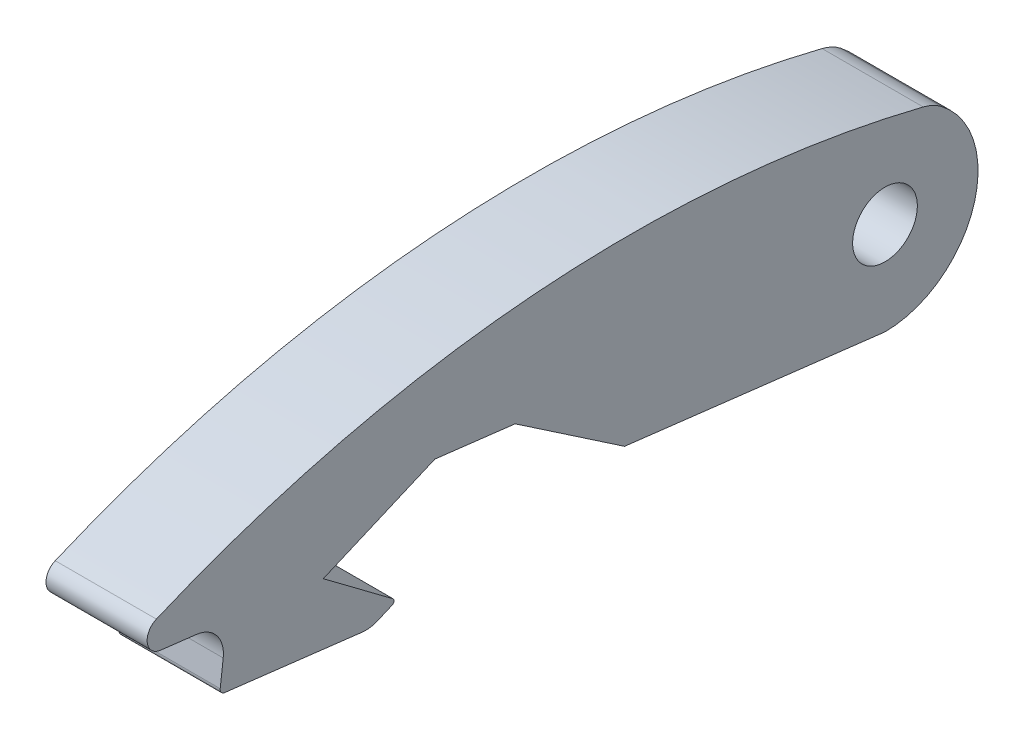
SolidWorks part; units mm, degrees
ref_plane "Front Plane" through (0, 0, 0) normal (1, 0, 0) x (0, 1, 0)
ref_plane "Top Plane" through (0, 0, 0) normal (0, 0, 1) x (0, 1, 0)
ref_plane "Right Plane" through (0, 0, 0) normal (0, 1, 0) x (-1, 0, 0)
sketch "Sketch2" plane through (0, 0, 0) normal (1, 0, 0) x (0, 1, 0)
  line L0 (0, 38.5) -> (-0.7118, 32.5424)
  line L1 (0, 0) -> (0, -1.2336) construction
  line L2 (3.9837, -2.3) -> (0, 0) construction
  line L3 (-0.7118, 32.5424) -> (-3.6906, 32.8983)
  line L6 (-4.877, 22.9689) -> (-1.2817, 27.7725)
  line L8 (-3.0613, 12.8784) -> (-4.6, 0)
  line L9 (-3.6906, 32.8983) -> (-4.877, 22.9689)
  line L10 (-1.2817, 27.7725) -> (1.0806, 22.2571)
  line L11 (-4.877, 22.9689) -> (1.0806, 22.2571) construction
  line L12 (-3.0613, 12.8784) -> (0.6061, 18.2853)
  line L13 (0.6061, 18.2853) -> (1.0806, 22.2571)
  circle A0 centre (0, 0) radius 1.6
  arc A1 (-4.6, 0) -> (3.9837, -2.3) centre (0, 0) ccw
  arc A2 (0, 38.5) -> (3.9837, -2.3) centre (-54.1316, 12.6201) cw
  point P5 (0, 38.5)
  point P6 (5.4008, 20.0962)
  point P8 (-3.0613, 12.8784)
  point P15 (0, 0)
  dimension "D1" = 3.2
  dimension "D2" = 38.5
  dimension "D3" = 4.6
  dimension "D4" = 60
  dimension "D5" = 60
  dimension "D6" = 20.8092
  dimension "D7" = 10
  dimension "D8" = 30
  dimension "D9" = 3
  dimension "D10" = 6
  dimension "D11" = 6
  dimension "D12" = 1.2336
  dimension "D13" = 15
  dimension "D15" = 60
  dimension "D16" = 4
extrude "Boss-Extrude1" add sketch "Sketch2" along normal blind 5
fillet "Fillet2" radius 1.5 1 edges at (2.5, -0.7118, 32.5424)
chamfer "Chamfer1" distance 2.5 angle 30 1 edges at (2.5, -4.877, 22.9689)
fillet "Fillet3" radius 1.5 1 edges at (2.5, -4.5804, 25.4513)
fillet "Fillet4" radius 0.25 1 edges at (2.5, -3.6906, 32.8983)
fillet "Fillet5" radius 0.15 1 edges at (2.5, -4.0121, 24.1245)
fillet "Fillet6" radius 0.75 1 edges at (2.5, 0, 38.5)
fillet "Fillet7" radius 2.5 1 edges at (2.5, 3.9837, -2.3)
